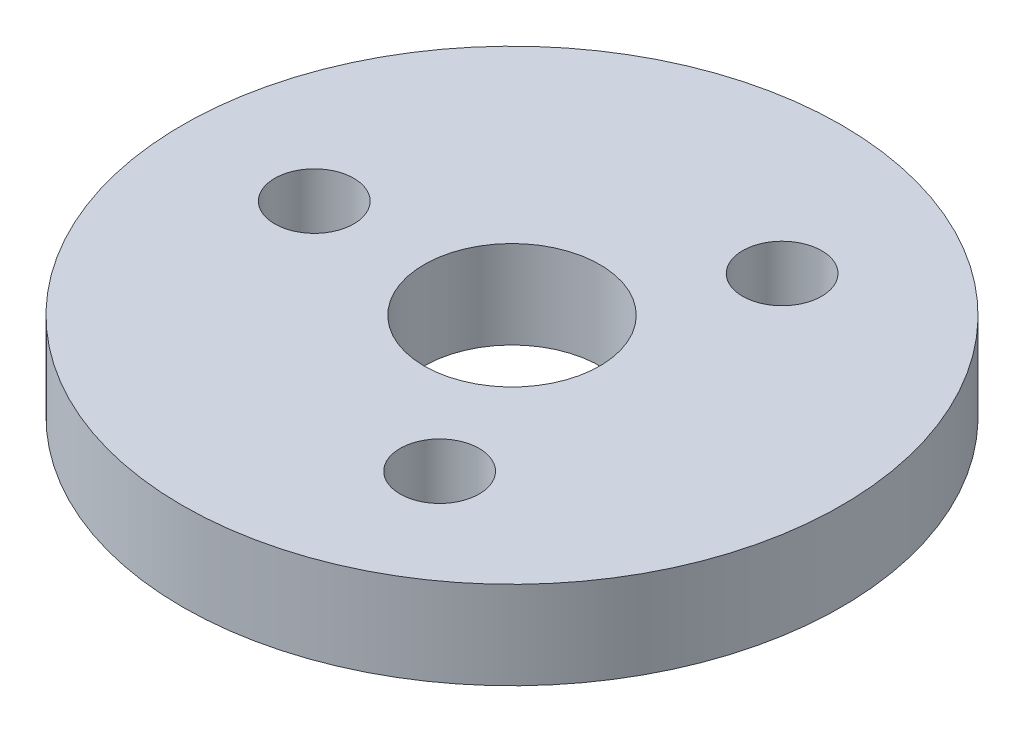
SolidWorks part; units mm, degrees
ref_plane "Alzado" through (0, 0, 0) normal (1, 0, 0) x (0, 1, 0)
ref_plane "Planta" through (0, 0, 0) normal (0, 0, 1) x (0, 1, 0)
ref_plane "Vista lateral" through (0, 0, 0) normal (0, 1, 0) x (-1, 0, 0)
sketch "Croquis1" plane through (0, 0, 0) normal (0, 1, 0) x (-1, 0, 0)
  circle A0 centre (0, 0) radius 15
  circle A1 centre (0, 0) radius 4
  dimension "D1" = 30
  dimension "D2" = 8
extrude "Saliente-Extruir1" add sketch "Croquis1" along normal blind 4
sketch "Croquis2" plane through (0, 4, 0) normal (0, 1, 0) x (-1, 0, 0)
  circle A0 centre (0, 0) radius 9 construction
  point P3 (9, 0)
  point P6 (-4.5, -7.7942)
  point P7 (-4.5, 7.7942)
  point P8 (0, 0)
  dimension "D1" = 18
  dimension "D2" = 3
hole_wizard "Taladro de margen para M31" positions "Croquis2" profile "Croquis3" hole size "M3" standard "Ansi Metric"
sketch "Croquis3" plane through (4.5, 4, 7.7942) normal (1, 0, 0) x (0, 0, 1)
  line L0 (0, 0) -> (0, 6.0815)
  line L1 (0, 6.0815) -> (1.8, 5)
  line L2 (1.8, 5) -> (1.8, 0)
  line L5 (1.8, 0) -> (0, 0)
  line L10 (0, 6.0815) -> (-1.8, 5) construction
  line L11 (0, -6.35) -> (0, 107.95) construction
  dimension "Diámetro de taladro" = 3.6
  dimension "Profundidad de taladro" = 5
  dimension "Ángulo de perforador" = 118
